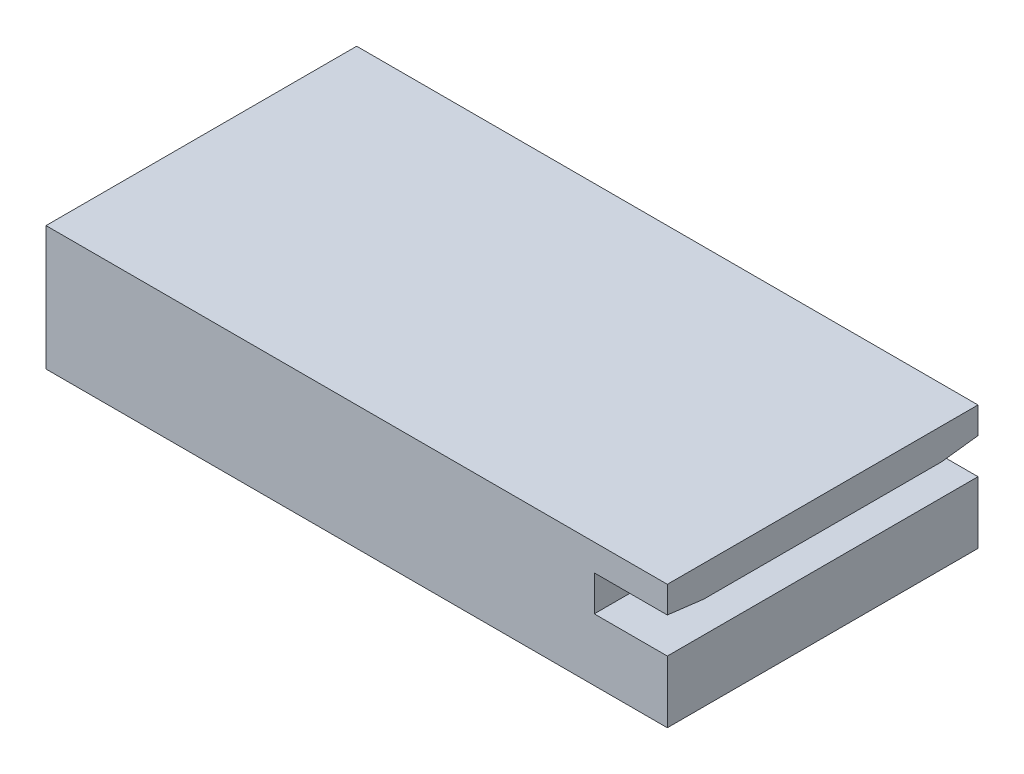
SolidWorks part; units mm, degrees
ref_plane "Piano frontale" through (0, 0, 0) normal (0, 0, 1) x (1, 0, 0)
ref_plane "Piano superiore" through (0, 0, 0) normal (0, 1, 0) x (1, 0, 0)
ref_plane "Piano destro" through (0, 0, 0) normal (1, 0, 0) x (0, 0, -1)
sketch "Schizzo2" plane through (0, 0, 0) normal (0, 1, 0) x (1, 0, 0)
  line L1 (-1000, 500) -> (1000, 500)
  line L2 (-1000, 500) -> (-1000, -500)
  line L3 (-1000, -500) -> (1000, -500)
  line L4 (1000, 500) -> (1000, -500)
  line L5 (-1000, 500) -> (1000, -500) construction
  line L6 (-1000, -500) -> (1000, 500) construction
  point P0 (0, 0)
  dimension "D1" = 2000
  dimension "D2" = 1000
extrude "Estrusione-Estrusione1" add sketch "Schizzo2" along normal blind 400
shell "Svuota1" thickness 40
sketch "Schizzo3" plane through (0, 40, 0) normal (0, 1, 0) x (1, 0, 0)
  line L1 (-160, 272.5) -> (160, 272.5)
  line L2 (-160, 272.5) -> (-160, -272.5)
  line L3 (-160, -272.5) -> (160, -272.5)
  line L4 (160, 272.5) -> (160, -272.5)
  line L5 (-160, 272.5) -> (160, -272.5) construction
  line L6 (-160, -272.5) -> (160, 272.5) construction
  point P0 (0, 0)
  dimension "D1" = 545
  dimension "D2" = 320
extrude "Estrusione-Estrusione2" add sketch "Schizzo3" along normal blind 285
sketch "Schizzo5" plane through (0, 0, 0) normal (0, -1, 0) x (1, 0, 0)
  line L0 (-1000, -500) -> (-1000, 500) construction
  line L1 (-780, 280) -> (780, 280) construction
  line L2 (-780, 280) -> (-780, -280) construction
  line L3 (-780, -280) -> (780, -280) construction
  line L4 (780, 280) -> (780, -280) construction
  line L5 (-780, 280) -> (780, -280) construction
  line L6 (-780, -280) -> (780, 280) construction
  line L7 (-1000, 500) -> (1000, 500) construction
  line L8 (0, 0) -> (0, 280) construction
  line L10 (0, 0) -> (780, 0) construction
  line L11 (1000, 500) -> (1000, -500) construction
  line L12 (1000, -500) -> (-1000, -500) construction
  circle A0 centre (-780, 280) radius 20
  circle A3 centre (780, -280) radius 20
  circle A4 centre (854.59, 280) radius 20
  circle A6 centre (-705.41, -280) radius 20
  point P0 (0, 0)
  dimension "D2" = 40
  dimension "D3" = 40
  dimension "D7" = 40
  dimension "D8" = 40
  dimension "D1" = 220
  dimension "D4" = 220
  dimension "D5" = 220
  dimension "D6" = 145.41
  dimension "D9" = 220
  dimension "D10" = 294.59
extrude "Taglio-Estrusione1" cut sketch "Schizzo5" against normal up to surface (40 mm away) up to face at (0, 40, 0)
ref_plane "Piano1" through (0, 200, 0) normal (0, 1, 0) x (1, 0, 0)
sketch "Schizzo7" plane through (0, 200, 0) normal (0, 1, 0) x (1, 0, 0)
  line L0 (0, 0) -> (1000, 0) construction
  line L1 (1000, -500) -> (1000, 500) construction
  line L4 (935, -32.5) -> (935, 32.5) construction
  line L7 (1000, -500) -> (1000, 500)
  line L8 (764.8439, 500) -> (764.8439, -500)
  line L9 (1000, 500) -> (-1000, 500) construction
  line L10 (1000, 500) -> (764.8439, 500)
  line L11 (764.8439, 500) -> (935, 32.5) construction
  line L12 (967.5, 0) -> (1000, -500) construction
  line L14 (764.8439, -500) -> (935, -32.5) construction
  line L15 (1000, -500) -> (764.8439, -500)
  point P6 (0, 0)
  point P9 (0, 0)
  point P10 (0, 0)
  point P15 (967.5, 0)
  point P16 (0, 0)
  point P17 (0, 0)
  dimension "D1" = 65
  dimension "D2" = 20
  dimension "D3" = 65
  dimension "D4" = 32.5
extrude "Taglio-Estrusione2" cut sketch "Schizzo7" along normal blind 100
sketch "Schizzo8" plane through (0, 0, -460) normal (0, 0, 1) x (1, 0, 0)
  line L0 (960, 320) -> (724.8439, 320)
  line L1 (764.8439, 200) -> (764.8439, 300) construction
  line L2 (724.8439, 320) -> (724.8439, 180)
  line L3 (724.8439, 180) -> (960, 180)
  line L4 (960, 200) -> (960, 40) construction
  line L6 (960, 300) -> (764.8439, 300) construction
  line L8 (550, 200) -> (-550, 200) construction
  line L9 (960, 320) -> (960, 300)
  line L10 (960, 300) -> (764.8439, 300)
  line L11 (764.8439, 300) -> (764.8439, 200)
  line L12 (764.8439, 200) -> (960, 200)
  line L13 (960, 200) -> (960, 180)
  point P5 (0, 0)
  point P9 (0, 0)
  dimension "D1" = 20
  dimension "D3" = 20
  dimension "D4" = 40
extrude "Estrusione-Estrusione4" add sketch "Schizzo8" along normal up to surface (920 mm away) up to face at (431.211, 225, 460)
sketch3d "Schizzo3D1"
  line L0 (1000, 400, 500) -> (-1000, 0, -500) construction
  line L1 (-1000, 400, 500) -> (1000, 0, -500) construction
  line L2 (1000, 400, -500) -> (-1000, 0, 500) construction
  line L3 (-1000, 400, -500) -> (1000, 0, 500) construction
  point P16 (0, 200, 0)
ref_point "Punto1"
sketch "Schizzo9" plane through (1000, 0, 0) normal (1, 0, 0) x (0, 0, -1)
  line L0 (-500, 300) -> (-500, 314.3923)
  line L1 (-500, 400) -> (-500, 300) construction
  line L3 (-500, 314.3923) -> (-382.7843, 300)
  line L4 (-500, 300) -> (500, 300) construction
  line L5 (-382.7843, 300) -> (-500, 300)
  line L7 (0, 220) -> (0, -220) construction
  line L8 (382.7843, 300) -> (500, 300)
  line L9 (500, 300) -> (500, 314.3923)
  line L10 (500, 314.3923) -> (382.7843, 300)
  point P7 (0, 0)
  point P11 (0, 0)
  dimension "D1" = 14.3923
  dimension "D2" = 117.2157
extrude "Taglio-Estrusione3" cut sketch "Schizzo9" against normal up to surface (235.1561 mm away) up to face at (764.8439, 250, 0)
